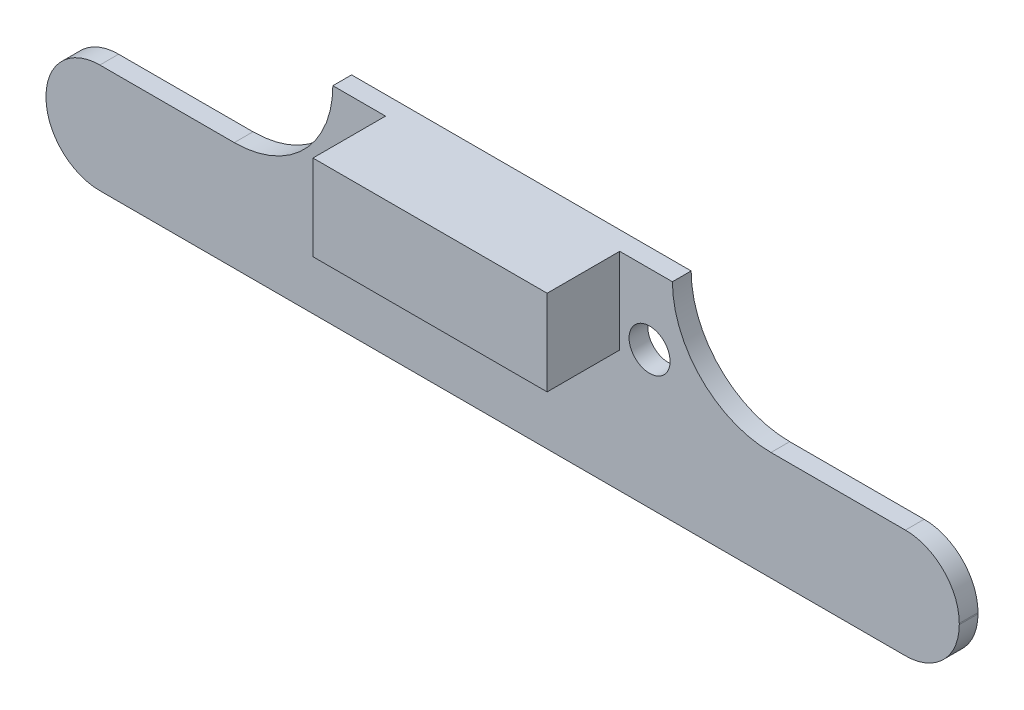
SolidWorks part; units mm, degrees
ref_plane "Plan de face" through (0, 0, 0) normal (0, 0, 1) x (1, 0, 0)
ref_plane "Plan de dessus" through (0, 0, 0) normal (0, 1, 0) x (1, 0, 0)
ref_plane "Plan de droite" through (0, 0, 0) normal (1, 0, 0) x (0, 0, -1)
sketch "Esquisse1" plane through (0, 0, 0) normal (0, 0, 1) x (1, 0, 0)
  line L0 (39, 9.3) -> (39, 0) construction
  line L1 (4.6, 0) -> (73.4, 0)
  line L2 (0, 4.6) -> (0, 4.7)
  line L3 (4.6, 9.3) -> (16.08, 9.3)
  line L4 (78, 4.6) -> (78, 4.7)
  line L5 (39, 9.3) -> (39, 17.72) construction
  line L6 (39, 17.72) -> (2.5031, 17.72) construction
  line L7 (24.5, 17.72) -> (24.5, 19.1172) construction
  line L8 (16.08, 17.72) -> (16.08, 9.3) construction
  line L9 (24.5, 17.72) -> (53.5, 17.72)
  line L10 (61.92, 9.3) -> (73.4, 9.3)
  line L11 (39, 11.72) -> (26.45, 11.72) construction
  arc A0 (73.4, 9.3) -> (78, 4.7) centre (73.4, 4.7) cw
  arc A1 (73.4, 0) -> (78, 4.6) centre (73.4, 4.6) ccw
  arc A2 (0, 4.6) -> (4.6, 0) centre (4.6, 4.6) ccw
  arc A3 (0, 4.7) -> (4.6, 9.3) centre (4.6, 4.7) cw
  arc A4 (24.5, 17.72) -> (16.08, 9.3) centre (16.08, 17.72) cw
  arc A5 (53.5, 17.72) -> (61.92, 9.3) centre (61.92, 17.72) ccw
  circle A6 centre (26.45, 11.72) radius 1.75
  circle A7 centre (51.55, 11.72) radius 1.75
  point P7 (78, 9.3)
  point P10 (78, 0)
  point P13 (0, 0)
  dimension "D3" = 4.6
  dimension "D1" = 9.3
  dimension "D2" = 78
  dimension "D4" = 14.5
  dimension "D5" = 12.55
  dimension "D6" = 8.42
  dimension "D7" = 6
extrude "Boss.-Extru.1" add sketch "Esquisse1" along normal blind 1.6
sketch "Esquisse2" plane through (0, 0, 1.6) normal (0, 0, 1) x (1, 0, 0)
  line L0 (39, 17.72) -> (39, 10.42) construction
  line L1 (53.5, 17.72) -> (24.5, 17.72) construction
  line L3 (29, 10.42) -> (49, 10.42)
  line L4 (29, 10.42) -> (29, 17.72)
  line L5 (29, 17.72) -> (49, 17.72)
  line L6 (49, 10.42) -> (49, 17.72)
  line L7 (29, 10.42) -> (49, 17.72) construction
  line L8 (29, 17.72) -> (49, 10.42) construction
  point P4 (39, 14.07)
  dimension "D1" = 7.3
  dimension "D2" = 20
extrude "Boss.-Extru.2" add sketch "Esquisse2" along normal blind 6.2
